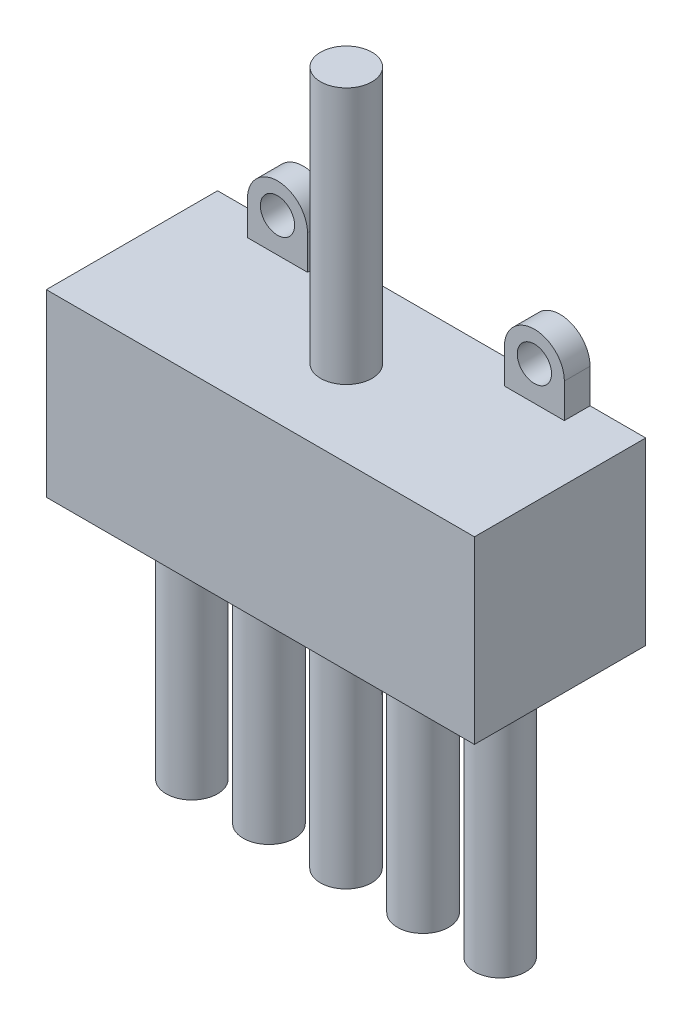
SolidWorks part; units mm, degrees
ref_plane "前视基准面" through (0, 0, 0) normal (0, 0, 1) x (1, 0, 0)
ref_plane "上视基准面" through (0, 0, 0) normal (0, 1, 0) x (1, 0, 0)
ref_plane "右视基准面" through (0, 0, 0) normal (1, 0, 0) x (0, 0, -1)
sketch "草图1" plane through (0, 0, 0) normal (0, 0, 1) x (1, 0, 0)
  line L0 (0, 0) -> (0, 41.0024) construction
  line L2 (-25, 10.5) -> (25, 10.5)
  line L3 (-25, 10.5) -> (-25, -10.5)
  line L4 (-25, -10.5) -> (25, -10.5)
  line L5 (25, 10.5) -> (25, -10.5)
  line L6 (-25, 10.5) -> (25, -10.5) construction
  line L7 (-25, -10.5) -> (25, 10.5) construction
  dimension "D1" = 50
  dimension "D2" = 21
extrude "凸台-拉伸1" add sketch "草图1" along normal blind 20
sketch "草图2" plane through (0, -10.5, 0) normal (0, -1, 0) x (1, 0, 0)
  line L0 (0, 0) -> (0, 22.5833) construction
  line L2 (25, 10) -> (-25, 10) construction
  line L3 (25, 20) -> (25, 0) construction
  line L4 (-25, 20) -> (-25, 0) construction
  circle A0 centre (0, 10) radius 3
  circle A1 centre (9, 10) radius 3
  circle A2 centre (18, 10) radius 3
  circle A3 centre (-18, 10) radius 3
  circle A4 centre (-9, 10) radius 3
  dimension "D1" = 6
  dimension "D2" = 3
extrude "凸台-拉伸2" add sketch "草图2" along normal blind 30 separate body
sketch "草图3" plane through (0, 10.5, 0) normal (0, 1, 0) x (1, 0, 0)
  circle A0 centre (0, -9.9639) radius 3
  dimension "D1" = 6
extrude "凸台-拉伸3" add sketch "草图3" along normal blind 30 separate body
sketch "草图4" plane through (0, 0, 0) normal (0, 0, -1) x (-1, 0, 0)
  line L0 (0, 0) -> (0, 31.6606) construction
  line L1 (-25, 10.5) -> (25, 10.5) construction
  line L2 (-18.5, 14.5) -> (-18.5, 10.5)
  line L3 (-11.5, 14.5) -> (-11.5, 10.5)
  line L4 (-18.5, 10.5) -> (-11.5, 10.5)
  line L5 (18.5, 10.5) -> (11.5, 10.5)
  line L6 (11.5, 14.5) -> (11.5, 10.5)
  line L7 (18.5, 14.5) -> (18.5, 10.5)
  circle A0 centre (-15, 14.5) radius 2
  arc A1 (-11.5, 14.5) -> (-18.5, 14.5) centre (-15, 14.5) ccw
  arc A2 (11.5, 14.5) -> (18.5, 14.5) centre (15, 14.5) cw
  circle A3 centre (15, 14.5) radius 2
  dimension "D3" = 4
  dimension "D4" = 7
  dimension "D1" = 15
  dimension "D2" = 4
extrude "凸台-拉伸4" add sketch "草图4" against normal blind 3 separate body
equation "\"A\"= \"代号代码\""
equation "\"B\"= \"名称代码\""
